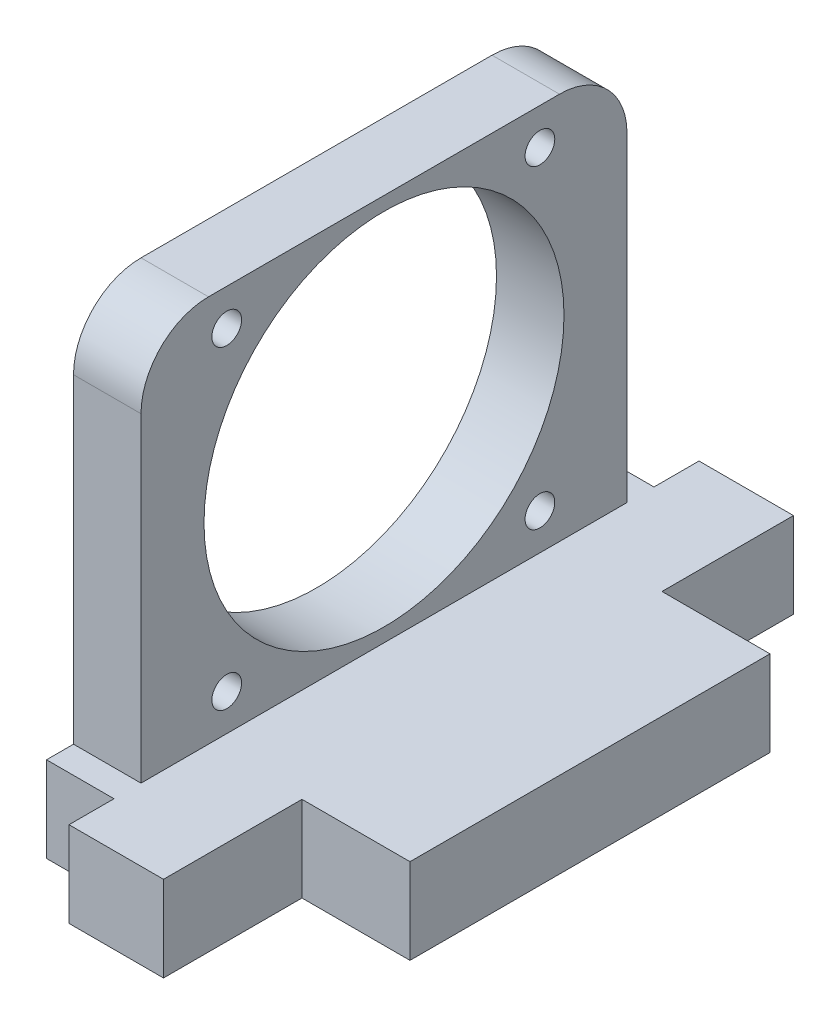
SolidWorks part; units mm, degrees
ref_plane "Front Plane" through (0, 0, 0) normal (0, 0, 1) x (1, 0, 0)
ref_plane "Top Plane" through (0, 0, 0) normal (0, 1, 0) x (1, 0, 0)
ref_plane "Right Plane" through (0, 0, 0) normal (1, 0, 0) x (0, 0, -1)
sketch "Sketch1" plane through (0, 0, 0) normal (0, 0, 1) x (1, 0, 0)
  line L0 (0, 0) -> (60, 0)
  line L5 (60, 0) -> (60, 19)
  line L6 (60, 19) -> (15, 19)
  line L7 (15, 19) -> (15, 105.1)
  line L8 (15, 105.1) -> (0, 105.1)
  line L9 (0, 105.1) -> (0, 0)
  dimension "D1" = 86.1
  dimension "D2" = 19
  dimension "D3" = 15
  dimension "D4" = 45
extrude "Boss-Extrude1" add sketch "Sketch1" along normal blind 120
sketch "Sketch2" plane through (15, 0, 0) normal (1, 0, 0) x (0, 0, -1)
  line L0 (-60, 105.1) -> (-60, 19) construction
  line L1 (-120, 105.1) -> (0, 105.1) construction
  line L2 (-120, 19) -> (0, 19) construction
  line L3 (0, 62.05) -> (-120, 62.05) construction
  line L4 (0, 19) -> (0, 105.1) construction
  line L5 (-120, 19) -> (-120, 105.1) construction
  line L7 (-94.95, 27.1) -> (-25.05, 27.1) construction
  line L8 (-94.95, 27.1) -> (-94.95, 97) construction
  line L9 (-94.95, 97) -> (-25.05, 97) construction
  line L10 (-25.05, 27.1) -> (-25.05, 97) construction
  line L11 (-94.95, 27.1) -> (-25.05, 97) construction
  line L12 (-94.95, 97) -> (-25.05, 27.1) construction
  circle A0 centre (-60, 62.05) radius 40
  circle A2 centre (-94.95, 97) radius 3.3
  circle A3 centre (-25.35, 97) radius 3.3
  circle A4 centre (-94.95, 27.1) radius 3.3
  circle A5 centre (-25.35, 27.1) radius 3.3
  dimension "D1" = 69.9
  dimension "D2" = 80
  dimension "D5" = 6.6
  dimension "D4" = 69.9
  dimension "D3" = 2
extrude "Cut-Extrude1" cut sketch "Sketch2" against normal through all
sketch "Sketch3" plane through (0, 19, 0) normal (0, 1, 0) x (1, 0, 0)
  line L0 (15, -120) -> (15, 0) construction
  line L1 (0, 0) -> (15, 0)
  line L2 (0, 0) -> (0, -6)
  line L3 (0, -6) -> (15, -6)
  line L4 (15, 0) -> (15, -6)
  line L5 (0, -120) -> (0, 0) construction
  line L6 (15, -120) -> (0, -120)
  line L7 (15, -120) -> (15, -114)
  line L8 (15, -114) -> (0, -114)
  line L9 (0, -120) -> (0, -114)
  dimension "D1" = 6
  dimension "D2" = 6
extrude "Cut-Extrude4" cut sketch "Sketch3" along normal up to surface (86.1 mm away) up to face at (7.5, 105.1, 60)
fillet "Fillet1" radius 15 2 edges at (7.5, 105.1, 6) (7.5, 105.1, 114)
sketch "Sketch4" plane through (0, 19, 0) normal (0, 1, 0) x (1, 0, 0)
  line L0 (60, -120) -> (60, 0) construction
  line L1 (60, -120) -> (36, -120)
  line L2 (60, -120) -> (60, -99.2244)
  line L3 (60, -99.2244) -> (36, -99.2244)
  line L4 (36, -120) -> (36, -99.2244)
  line L5 (60, 0) -> (36, 0)
  line L6 (60, 0) -> (60, -19.2244)
  line L7 (60, -19.2244) -> (36, -19.2244)
  line L8 (36, 0) -> (36, -19.2244)
  line L9 (15, -114) -> (15, -6) construction
  line L10 (60, 0) -> (0, 0) construction
  dimension "D1" = 80
  dimension "D2" = 21
extrude "Cut-Extrude5" cut sketch "Sketch4" against normal through all
sketch "Sketch6" plane through (0, 19, 0) normal (0, 1, 0) x (1, 0, 0)
  line L0 (15, -114) -> (15, -6) construction
  line L1 (36, 0) -> (15, 0)
  line L2 (36, 0) -> (36, 10)
  line L3 (36, 10) -> (15, 10)
  line L4 (15, 0) -> (15, 10)
  line L5 (36, -130) -> (15, -130)
  line L6 (36, -130) -> (36, -120)
  line L7 (36, -120) -> (15, -120)
  line L8 (15, -130) -> (15, -120)
  dimension "D1" = 10
  dimension "D2" = 10
extrude "Boss-Extrude2" add sketch "Sketch6" against normal up to surface (19 mm away) up to face at (33, 0, 59.6122)
